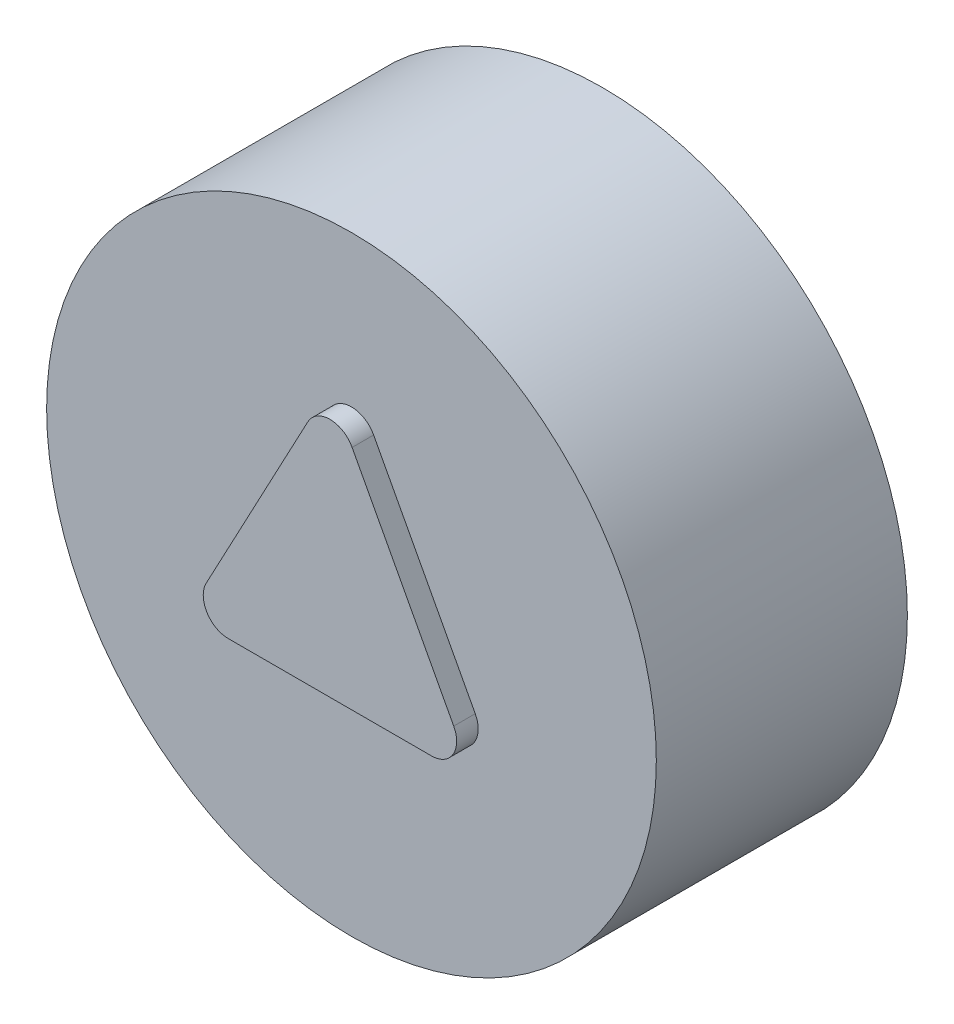
SolidWorks part; units mm, degrees
ref_plane "Front Plane" through (0, 0, 0) normal (0, 0, 1) x (1, 0, 0)
ref_plane "Top Plane" through (0, 0, 0) normal (0, 1, 0) x (1, 0, 0)
ref_plane "Right Plane" through (0, 0, 0) normal (1, 0, 0) x (0, 0, -1)
sketch "Sketch1" plane through (0, 0, 0) normal (0, 0, 1) x (1, 0, 0)
  circle A0 centre (0, 0) radius 8.5
  dimension "D1" = 17
extrude "Boss-Extrude1" add sketch "Sketch1" along normal blind 7
sketch "Sketch2" plane through (0, 0, 7) normal (0, 0, 1) x (1, 0, 0)
  line L12 (-3.451, -1.3947) -> (-0.6176, 3.9178)
  line L13 (0.6176, 3.9178) -> (3.451, -1.3947)
  line L14 (2.8333, -2.4241) -> (-2.8333, -2.4241)
  line L15 (0, 5.0759) -> (0, -2.4241) construction
  line L16 (0, -3.85) -> (0, 3.85) construction
  arc A0 (3.451, -1.3947) -> (2.8333, -2.4241) centre (2.8333, -1.7241) cw
  arc A1 (-3.451, -1.3947) -> (-2.8333, -2.4241) centre (-2.8333, -1.7241) ccw
  arc A2 (-0.6176, 3.9178) -> (0.6176, 3.9178) centre (0, 3.5884) cw
  point P7 (0, 5.0759)
  point P10 (4, -2.4241)
  point P13 (-4, -2.4241)
  dimension "D3" = 0.7
  dimension "D1" = 7.5
  dimension "D2" = 8
extrude "Boss-Extrude2" add sketch "Sketch2" along normal blind 0.6
sketch "Sketch3" plane through (0, 0, 0) normal (0, 0, -1) x (-1, 0, 0)
  circle A0 centre (0, 0) radius 5.8
  dimension "D1" = 11.6
extrude "Cut-Extrude1" cut sketch "Sketch3" against normal blind 4.15
